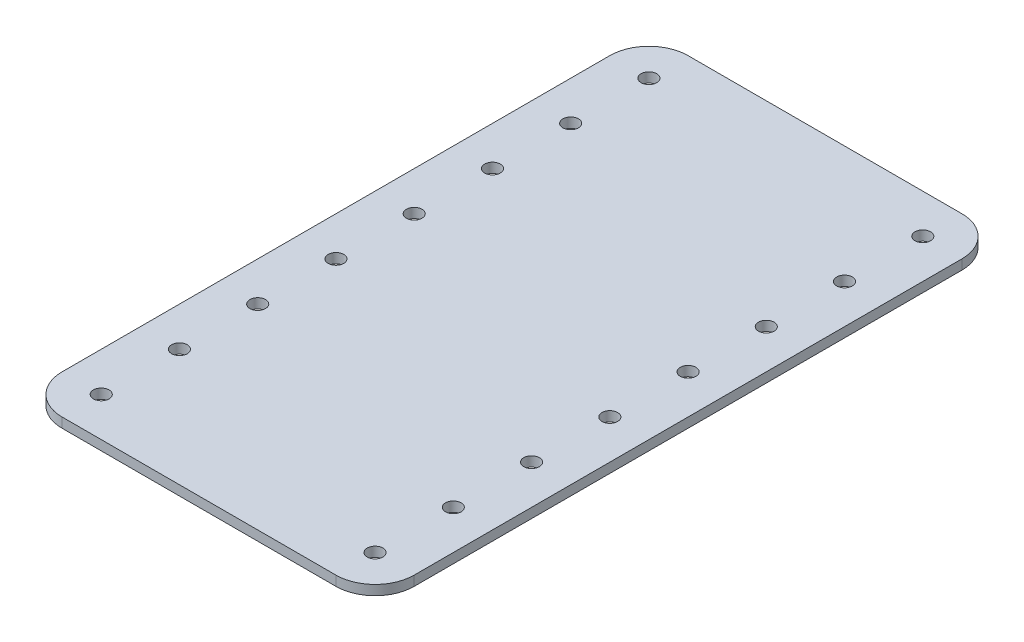
SolidWorks part; units mm, degrees
ref_plane "Front Plane" through (0, 0, 0) normal (0, 0, 1) x (1, 0, 0)
ref_plane "Top Plane" through (0, 0, 0) normal (0, 1, 0) x (1, 0, 0)
ref_plane "Right Plane" through (0, 0, 0) normal (1, 0, 0) x (0, 0, -1)
sketch "Sketch1" plane through (0, 0, 0) normal (0, 1, 0) x (1, 0, 0)
  line L1 (-57.15, -101.6) -> (57.15, -101.6)
  line L2 (-57.15, -101.6) -> (-57.15, 101.6)
  line L3 (-57.15, 101.6) -> (57.15, 101.6)
  line L4 (57.15, -101.6) -> (57.15, 101.6)
  line L5 (-57.15, -101.6) -> (57.15, 101.6) construction
  line L6 (-57.15, 101.6) -> (57.15, -101.6) construction
  point P0 (0, 0)
  dimension "D1" = 114.3
  dimension "D2" = 203.2
extrude "Boss-Extrude1" add sketch "Sketch1" along normal blind 3.175
sketch "Sketch2" plane through (0, 3.175, 0) normal (0, 1, 0) x (1, 0, 0)
  line L0 (57.15, 101.6) -> (-57.15, 101.6) construction
  line L1 (-57.15, 101.6) -> (-57.15, -101.6) construction
  line L2 (-57.15, -101.6) -> (57.15, -101.6) construction
  line L3 (0, 0) -> (0, 28.6343) construction
  circle A0 centre (-44.45, 88.9) radius 2.54
  circle A1 centre (-44.45, 63.5) radius 2.54
  circle A2 centre (-44.45, 38.1) radius 2.54
  circle A3 centre (-44.45, 12.7) radius 2.54
  circle A4 centre (-44.45, -12.7) radius 2.54
  circle A5 centre (-44.45, -38.1) radius 2.54
  circle A6 centre (-44.45, -63.5) radius 2.54
  circle A7 centre (-44.45, -88.9) radius 2.54
  circle A8 centre (44.45, -88.9) radius 2.54
  circle A9 centre (44.45, -63.5) radius 2.54
  circle A10 centre (44.45, -38.1) radius 2.54
  circle A11 centre (44.45, -12.7) radius 2.54
  circle A12 centre (44.45, 12.7) radius 2.54
  circle A13 centre (44.45, 38.1) radius 2.54
  circle A14 centre (44.45, 63.5) radius 2.54
  circle A15 centre (44.45, 88.9) radius 2.54
  dimension "D1" = 5.08
  dimension "D2" = 12.7
  dimension "D3" = 12.7
  dimension "D4" = 8
  dimension "D5" = 12.7
extrude "Cut-Extrude1" cut sketch "Sketch2" against normal blind 3.175
fillet "Fillet1" radius 12.7 4 edges at (-57.15, 1.5875, -101.6) (57.15, 1.5875, -101.6) (57.15, 1.5875, 101.6) (-57.15, 1.5875, 101.6)
